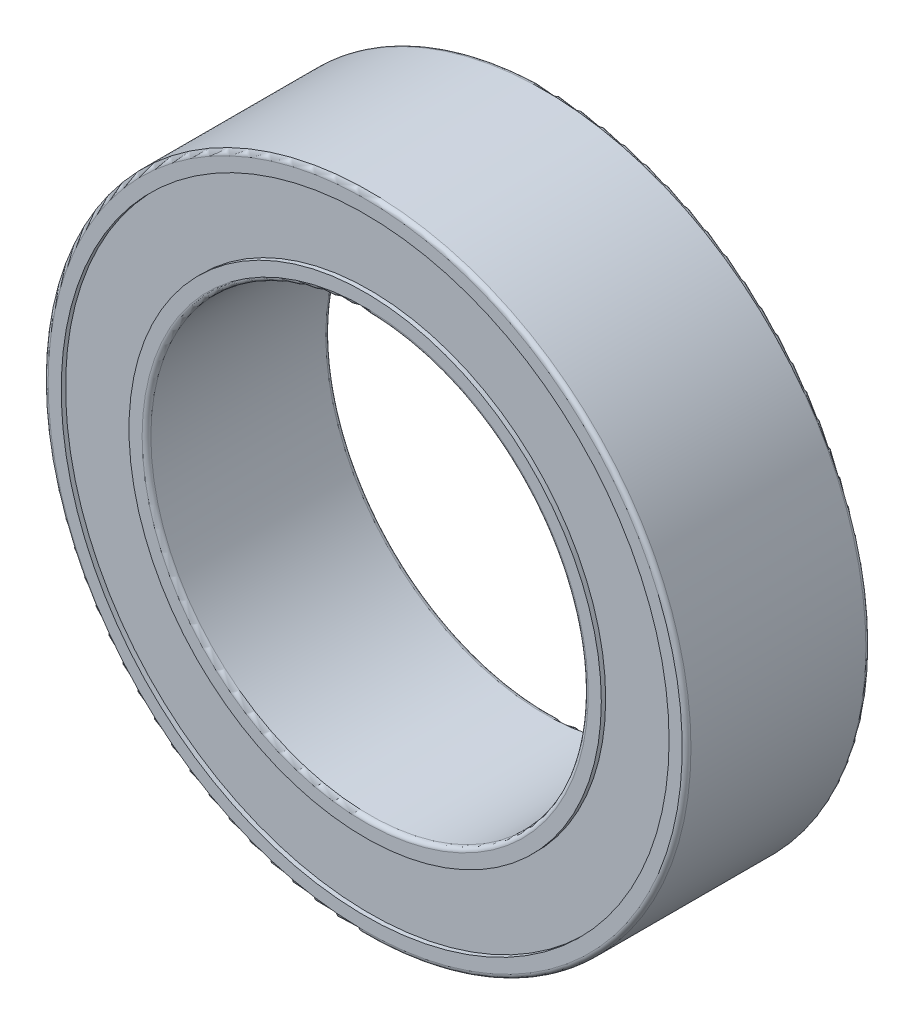
SolidWorks part; units mm, degrees
material "Plain Carbon Steel"
ref_plane "Front Plane" through (0, 0, 0) normal (0, 0, 1) x (1, 0, 0)
ref_plane "Top Plane" through (0, 0, 0) normal (0, 1, 0) x (1, 0, 0)
ref_plane "Right Plane" through (0, 0, 0) normal (1, 0, 0) x (0, 0, -1)
sketch "Sketch1" plane through (0, 0, 0) normal (1, 0, 0) x (0, 0, -1)
  line L0 (-14.88, 0) -> (16.8, 0) construction
  line L1 (-2.1, 5) -> (-2.1, 5.4)
  line L2 (-2.1, 5.4) -> (-2, 5.4)
  line L3 (2.1, 5) -> (2.1, 5.4)
  line L4 (2.1, 5.4) -> (2, 5.4)
  line L5 (-2, 5.4) -> (-2, 6.95)
  line L6 (-2, 6.95) -> (-2.1, 6.95)
  line L7 (2, 5.4) -> (2, 6.95)
  line L8 (2, 6.95) -> (2.1, 6.95)
  line L9 (-2.1, 6.95) -> (-2.1, 7.35)
  line L10 (-2.1, 7.35) -> (2.1, 7.35)
  line L11 (0, 7.35) -> (0, 0) construction
  line L12 (-2.1, 5) -> (2.1, 5)
  line L13 (-2, 6.175) -> (0, 6.175) construction
  line L14 (2.1, 6.95) -> (2.1, 7.35)
  point P7 (0, 0)
  point P8 (-1.2834, 6.95)
  point P11 (0, 5)
  dimension "D1" = 10
  dimension "D2" = 14.7
  dimension "D3" = 0.4
  dimension "D4" = 0.1
  dimension "D5" = 4.2
revolve "Revolve1" add sketch "Sketch1" angle 360 about L0
fillet "Fillet1" radius 0.1 4 edges at (5, 0, 2.1) (5, 0, -2.1) (7.35, 0, -2.1) (7.35, 0, 2.1)
